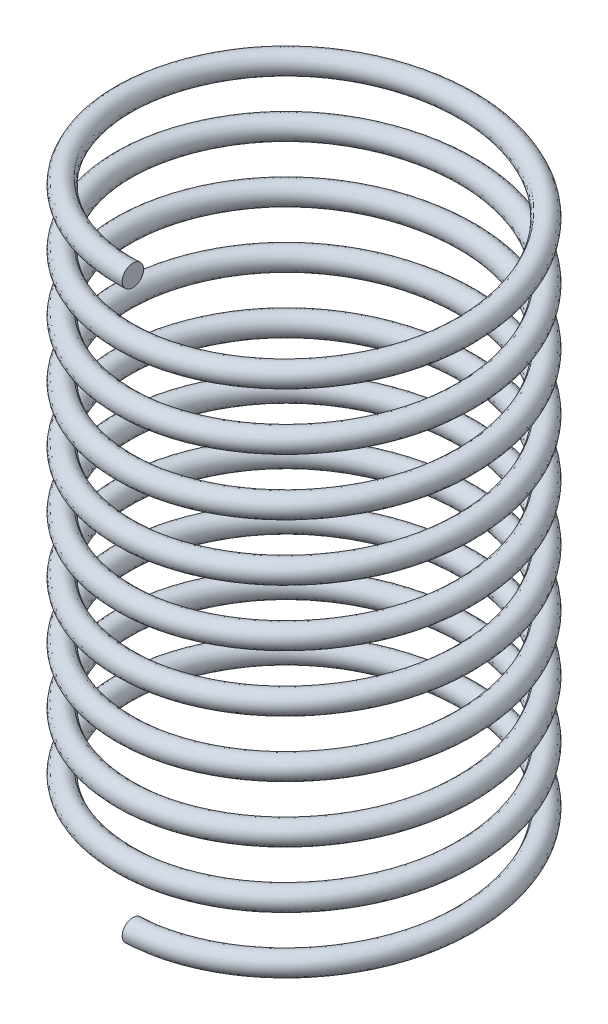
SolidWorks part; units mm, degrees
ref_plane "Front Plane" through (0, 0, 0) normal (0, 0, 1) x (1, 0, 0)
ref_plane "Top Plane" through (0, 0, 0) normal (0, 1, 0) x (1, 0, 0)
ref_plane "Right Plane" through (0, 0, 0) normal (1, 0, 0) x (0, 0, -1)
sketch "Sketch1" plane through (0, 0, 0) normal (0, 1, 0) x (1, 0, 0)
  circle A0 centre (0, 0) radius 1.6
  dimension "D1" = 3.2
curve "Helix/Spiral1" pitch 0.53 height 5.3 turns 10
sketch "Sketch3" plane through (0, 0, 0) normal (1, 0, 0) x (0, 0, -1)
  circle A0 centre (-1.6, 0) radius 0.1
  spline S0 degree 3 poles (-1.6, 0) (-1.6, 0.011) (-1.5167, 0.0332) (-1.1608, 0.0662) (-0.4507, 0.1104) (0.4507, 0.1546) (1.1608, 0.1987) (1.5167, 0.2319) (1.6417, 0.265) (1.5167, 0.2981) (1.1608, 0.3312) (0.4507, 0.3754) (-0.4507, 0.4196) (-1.1608, 0.4637) (-1.5167, 0.4969) (-1.6417, 0.53) (-1.5167, 0.5631) (-1.1608, 0.5962) (-0.4507, 0.6404) (0.4507, 0.6846) (1.1608, 0.7287) (1.5167, 0.7619) (1.6417, 0.795) (1.5167, 0.8281) (1.1608, 0.8612) (0.4507, 0.9054) (-0.4507, 0.9496) (-1.1608, 0.9937) (-1.5167, 1.0269) (-1.6417, 1.06) (-1.5167, 1.0931) (-1.1608, 1.1262) (-0.4507, 1.1704) (0.4507, 1.2146) (1.1608, 1.2587) (1.5167, 1.2919) (1.6417, 1.325) (1.5167, 1.3581) (1.1608, 1.3912) (0.4507, 1.4354) (-0.4507, 1.4796) (-1.1608, 1.5237) (-1.5167, 1.5569) (-1.6417, 1.59) (-1.5167, 1.6231) (-1.1608, 1.6562) (-0.4507, 1.7004) (0.4507, 1.7446) (1.1608, 1.7887) (1.5167, 1.8219) (1.6417, 1.855) (1.5167, 1.8881) (1.1608, 1.9212) (0.4507, 1.9654) (-0.4507, 2.0096) (-1.1608, 2.0537) (-1.5167, 2.0869) (-1.6417, 2.12) (-1.5167, 2.1531) (-1.1608, 2.1862) (-0.4507, 2.2304) (0.4507, 2.2746) (1.1608, 2.3188) (1.5167, 2.3519) (1.6417, 2.385) (1.5167, 2.4181) (1.1608, 2.4513) (0.4507, 2.4954) (-0.4507, 2.5396) (-1.1608, 2.5838) (-1.5167, 2.6169) (-1.6417, 2.65) (-1.5167, 2.6831) (-1.1608, 2.7163) (-0.4507, 2.7604) (0.4507, 2.8046) (1.1608, 2.8488) (1.5167, 2.8819) (1.6417, 2.915) (1.5167, 2.9481) (1.1608, 2.9813) (0.4507, 3.0254) (-0.4507, 3.0696) (-1.1608, 3.1138) (-1.5167, 3.1469) (-1.6417, 3.18) (-1.5167, 3.2131) (-1.1608, 3.2463) (-0.4507, 3.2904) (0.4507, 3.3346) (1.1608, 3.3788) (1.5167, 3.4119) (1.6417, 3.445) (1.5167, 3.4781) (1.1608, 3.5113) (0.4507, 3.5554) (-0.4507, 3.5996) (-1.1608, 3.6438) (-1.5167, 3.6769) (-1.6417, 3.71) (-1.5167, 3.7431) (-1.1608, 3.7763) (-0.4507, 3.8204) (0.4507, 3.8646) (1.1608, 3.9088) (1.5167, 3.9419) (1.6417, 3.975) (1.5167, 4.0081) (1.1608, 4.0413) (0.4507, 4.0854) (-0.4507, 4.1296) (-1.1608, 4.1738) (-1.5167, 4.2069) (-1.6417, 4.24) (-1.5167, 4.2731) (-1.1608, 4.3063) (-0.4507, 4.3504) (0.4507, 4.3946) (1.1608, 4.4388) (1.5167, 4.4719) (1.6417, 4.505) (1.5167, 4.5381) (1.1608, 4.5713) (0.4507, 4.6154) (-0.4507, 4.6596) (-1.1608, 4.7038) (-1.5167, 4.7369) (-1.6417, 4.77) (-1.5167, 4.8031) (-1.1608, 4.8363) (-0.4507, 4.8804) (0.4507, 4.9246) (1.1608, 4.9688) (1.5167, 5.0019) (1.6417, 5.035) (1.5167, 5.0681) (1.1608, 5.1013) (0.4507, 5.1454) (-0.4507, 5.1896) (-1.1608, 5.2338) (-1.5167, 5.2668) (-1.6, 5.289) (-1.6, 5.3) knots 0 0 0 0 0.00625 0.0125 0.01875 0.03125 0.0375 0.04375 0.05 0.05625 0.0625 0.06875 0.08125 0.0875 0.09375 0.1 0.10625 0.1125 0.11875 0.13125 0.1375 0.14375 0.15 0.15625 0.1625 0.16875 0.18125 0.1875 0.19375 0.2 0.20625 0.2125 0.21875 0.23125 0.2375 0.24375 0.25 0.25625 0.2625 0.26875 0.28125 0.2875 0.29375 0.3 0.30625 0.3125 0.31875 0.33125 0.3375 0.34375 0.35 0.35625 0.3625 0.36875 0.38125 0.3875 0.39375 0.4 0.40625 0.4125 0.41875 0.43125 0.4375 0.44375 0.45 0.45625 0.4625 0.46875 0.48125 0.4875 0.49375 0.5 0.50625 0.5125 0.51875 0.53125 0.5375 0.54375 0.55 0.55625 0.5625 0.56875 0.58125 0.5875 0.59375 0.6 0.60625 0.6125 0.61875 0.63125 0.6375 0.64375 0.65 0.65625 0.6625 0.66875 0.68125 0.6875 0.69375 0.7 0.70625 0.7125 0.71875 0.73125 0.7375 0.74375 0.75 0.75625 0.7625 0.76875 0.78125 0.7875 0.79375 0.8 0.80625 0.8125 0.81875 0.83125 0.8375 0.84375 0.85 0.85625 0.8625 0.86875 0.88125 0.8875 0.89375 0.9 0.90625 0.9125 0.91875 0.93125 0.9375 0.94375 0.95 0.95625 0.9625 0.96875 0.98125 0.9875 0.99375 1 1 1 1 construction
  dimension "D1" = 0.2
sweep "Sweep1" add profiles "Sketch3" path "Helix/Spiral1"
